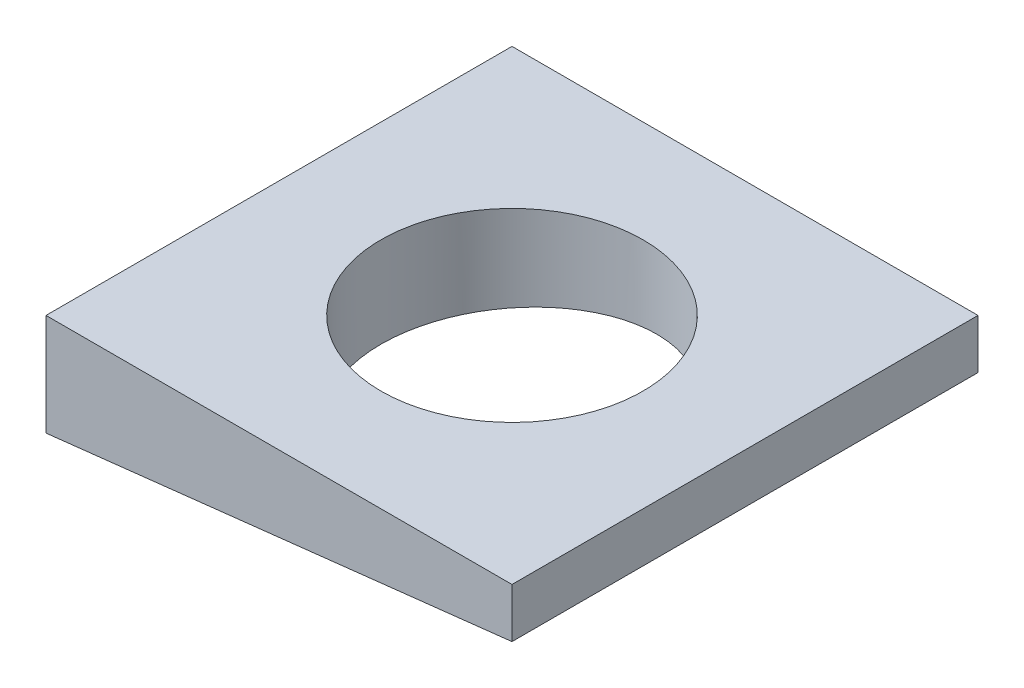
SolidWorks part; units mm, degrees
ref_plane "Přední rovina" through (0, 0, 0) normal (0, 0, 1) x (1, 0, 0)
ref_plane "Vrchní rovina" through (0, 0, 0) normal (0, 1, 0) x (1, 0, 0)
ref_plane "Pravá rovina" through (0, 0, 0) normal (1, 0, 0) x (0, 0, -1)
sketch "Skica1" plane through (0, 0, 0) normal (0, 0, 1) x (1, 0, 0)
  line L0 (0, 0) -> (16, 0)
  line L1 (16, 0) -> (16, -1.7)
  line L2 (16, -1.7) -> (0, -3.5)
  line L3 (0, -3.5) -> (0, 0)
  dimension "t" = 3.5
  dimension "t1" = 1.7
  dimension "a" = 16
extrude "Vysunout1" add sketch "Skica1" along normal blind 16
sketch "Skica2" plane through (0, 0, 0) normal (0, 1, 0) x (-1, 0, 0)
  line L0 (-16, 0) -> (0, 16) construction
  circle A0 centre (-8, 8) radius 4.5
  dimension "d1" = 9
extrude "Odebrat vysunutím1" cut sketch "Skica2" against normal through all
equation "\"D1@Vysunout1\" = \"a@Skica1\""
